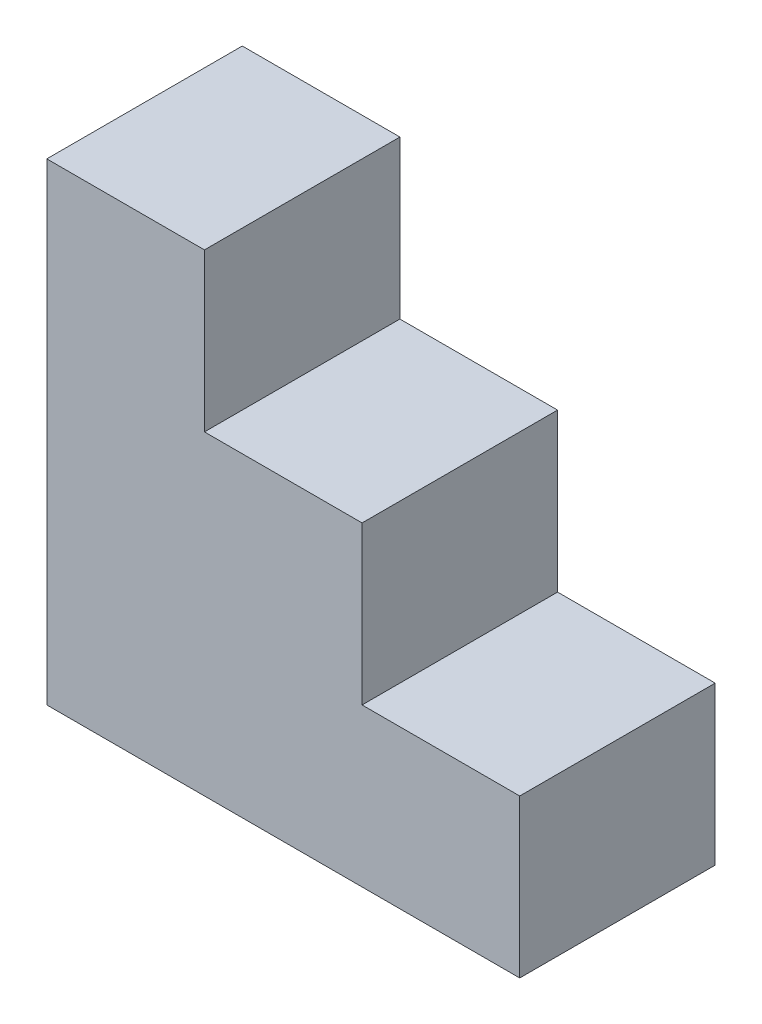
SolidWorks part; units mm, degrees
ref_plane "Front" through (0, 0, 0) normal (0, 0, 1) x (1, 0, 0)
ref_plane "Top" through (0, 0, 0) normal (0, 1, 0) x (1, 0, 0)
ref_plane "Right" through (0, 0, 0) normal (1, 0, 0) x (0, 0, -1)
sketch "Sketch1" plane through (0, 0, 0) normal (0, 0, 1) x (1, 0, 0)
  line L1 (0, 0) -> (30, 0)
  line L2 (0, 0) -> (0, 30)
  line L3 (0, 30) -> (10, 30)
  line L4 (30, 0) -> (30, 10)
  line L6 (10, 30) -> (10, 20)
  line L7 (20, 10) -> (30, 10)
  line L9 (10, 20) -> (20, 20)
  line L12 (20, 20) -> (20, 10)
  dimension "D1" = 30
  dimension "D2" = 30
  dimension "D3" = 10
  dimension "D4" = 10
extrude "Boss-Extrude1" add sketch "Sketch1" along normal blind 12.4
